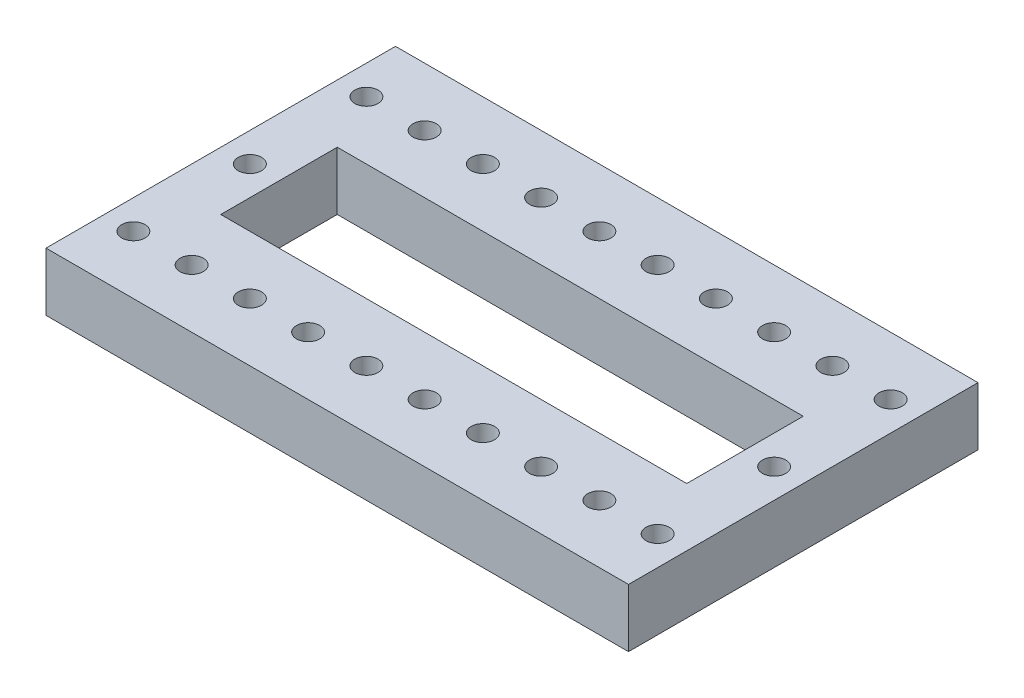
SolidWorks part; units mm, degrees
ref_plane "Front Plane" through (0, 0, 0) normal (0, 0, 1) x (1, 0, 0)
ref_plane "Top Plane" through (0, 0, 0) normal (0, 1, 0) x (1, 0, 0)
ref_plane "Right Plane" through (0, 0, 0) normal (1, 0, 0) x (0, 0, -1)
sketch "Sketch1" plane through (0, 0, 0) normal (0, 1, 0) x (1, 0, 0)
  line L0 (10, 40) -> (10, 20)
  line L1 (0, 0) -> (100, 0)
  line L2 (0, 0) -> (0, 60)
  line L3 (0, 60) -> (100, 60)
  line L4 (100, 0) -> (100, 60)
  line L5 (10, 20) -> (90, 20)
  line L6 (90, 20) -> (90, 40)
  line L7 (90, 40) -> (10, 40)
  circle A2 centre (5, 30) radius 2
  circle A7 centre (5, 50) radius 2
  circle A29 centre (5, 10) radius 2
  circle A30 centre (15, 50) radius 2
  circle A31 centre (15, 10) radius 2
  circle A32 centre (25, 50) radius 2
  circle A33 centre (25, 10) radius 2
  circle A34 centre (35, 50) radius 2
  circle A35 centre (35, 10) radius 2
  circle A36 centre (45, 50) radius 2
  circle A37 centre (45, 10) radius 2
  circle A38 centre (55, 50) radius 2
  circle A39 centre (55, 10) radius 2
  circle A40 centre (65, 50) radius 2
  circle A41 centre (65, 10) radius 2
  circle A42 centre (75, 50) radius 2
  circle A43 centre (75, 10) radius 2
  circle A44 centre (85, 50) radius 2
  circle A45 centre (85, 10) radius 2
  circle A46 centre (95, 50) radius 2
  circle A47 centre (95, 10) radius 2
  circle A48 centre (95, 30) radius 2
  dimension "D4" = 4
  dimension "D5" = 10
  dimension "D6" = 5
  dimension "D7" = 4
  dimension "D8" = 5
  dimension "D9" = 10
  dimension "D25" = 4
  dimension "D10" = 4
  dimension "D1" = 60
  dimension "D2" = 100
  dimension "D3" = 10
  dimension "D11" = 5
  dimension "D12" = 30
  dimension "D14" = 5
  dimension "D15" = 30
  dimension "D22" = 20
  dimension "D23" = 20
  dimension "D24" = 10
  dimension "D28" = 10
extrude "Boss-Extrude1" add sketch "Sketch1" along normal blind 10
